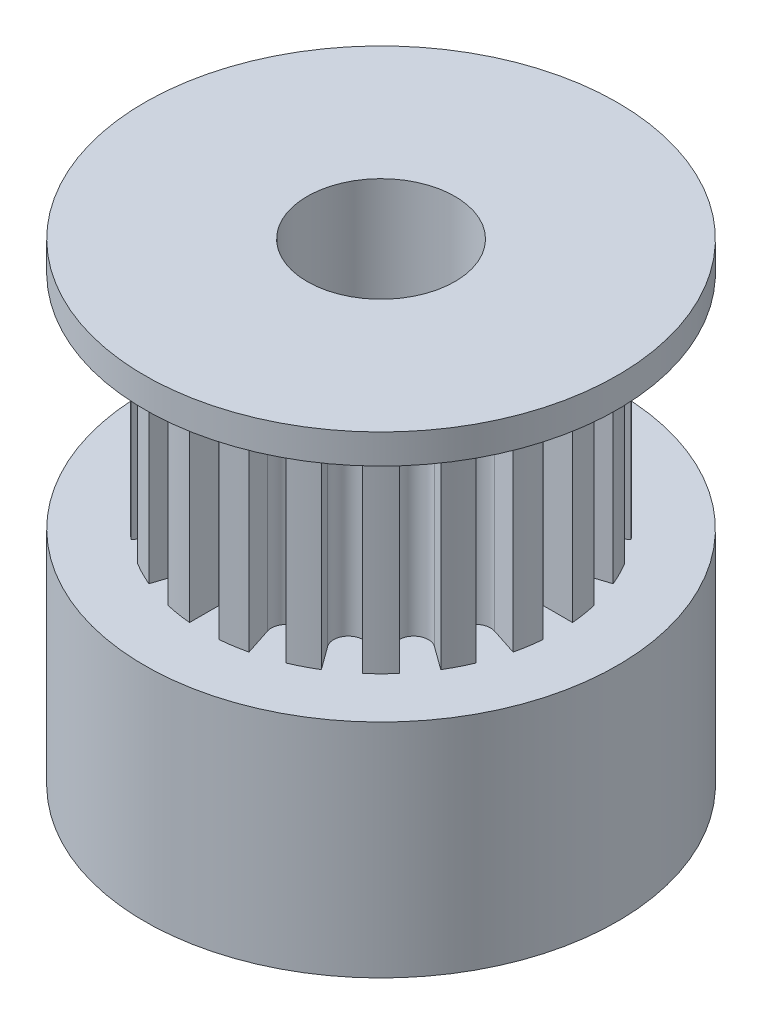
SolidWorks part; units mm, degrees
ref_plane "前视基准面" through (0, 0, 0) normal (0, 0, 1) x (1, 0, 0)
ref_plane "上视基准面" through (0, 0, 0) normal (0, 1, 0) x (1, 0, 0)
ref_plane "右视基准面" through (0, 0, 0) normal (1, 0, 0) x (0, 0, -1)
sketch "草图1" plane through (0, 0, 0) normal (0, 0, 1) x (1, 0, 0)
  line L0 (-8, 0) -> (0, 0)
  line L1 (0, 0) -> (0, 6.8875) construction
  line L3 (-8, -16) -> (-8, -8.5)
  line L4 (-8, -8.5) -> (-6, -8.5)
  line L5 (-6, -8.5) -> (-6, -1)
  line L6 (-6, -1) -> (-8, -1)
  line L7 (-8, -1) -> (-8, 0)
  line L15 (0, 0) -> (0, -16)
  line L16 (0, -16) -> (-8, -16)
  point P14 (0, 0)
  point P19 (0, -16)
  dimension "D1" = 1
  dimension "D2" = 7.5
  dimension "D3" = 8
  dimension "D4" = 8
  dimension "D5" = 16
  dimension "D6" = 2
revolve "旋转3" add sketch "草图1" angle 360 about L1
sketch "草图2" plane through (0, -1, 0) normal (0, -1, 0) x (1, 0, 0)
  line L1 (-0.5, 5) -> (0.5, 5)
  line L2 (-0.5, 5) -> (-0.5, 9)
  line L3 (-0.5, 9) -> (0.5, 9)
  line L4 (0.5, 5) -> (0.5, 9)
  circle A2 centre (0, 5) radius 0.5
  circle A3 centre (0, 0) radius 5
  circle A4 centre (0, 0) radius 5 construction
  dimension "D2" = 1
  dimension "D3" = 4
  dimension "D4" = 1
  dimension "D1" = 1
extrude "切除-拉伸1" cut sketch "草图2" along direction (0, -1, 0) on the side of the normal up to surface (7.5 mm away) contours A2 | L2 L3 L4 L1
pattern_circular "阵列(圆周)1" count 20 over 360 about axis through (0, 0, 0) along (0, 1, 0) of "切除-拉伸1"
sketch "草图3" plane through (0, 0, 0) normal (0, 1, 0) x (1, 0, 0)
  circle A0 centre (0, 0) radius 2.5
  dimension "D1" = 5
extrude "切除-拉伸2" cut sketch "草图3" against normal through all
ref_plane "基准面1" through (0, -4.75, 0) normal (0, -1, 0) x (-1, 0, 0)
